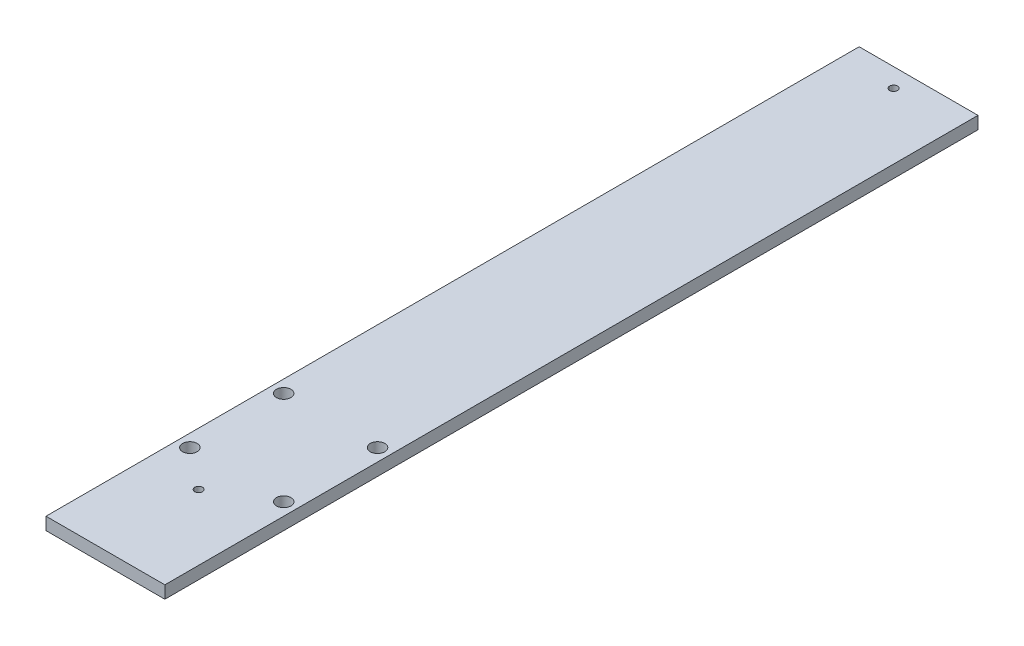
SolidWorks part; units mm, degrees
material "Alloy Steel"
ref_plane "Front" through (0, 0, 0) normal (0, 0, 1) x (1, 0, 0)
ref_plane "Top" through (0, 0, 0) normal (0, 1, 0) x (1, 0, 0)
ref_plane "Right" through (0, 0, 0) normal (1, 0, 0) x (0, 0, -1)
sketch "Sketch1" plane through (0, 0, 0) normal (0, 1, 0) x (1, 0, 0)
  line L1 (0, 0) -> (241.3, 0)
  line L2 (0, 0) -> (0, -1651)
  line L3 (0, -1651) -> (241.3, -1651)
  line L4 (241.3, 0) -> (241.3, -1651)
  dimension "D1" = 241.3
  dimension "D2" = 1651
extrude "Boss-Extrude1" add sketch "Sketch1" along normal blind 25.4
sketch "Sketch2" plane through (0, 25.4, 0) normal (0, 1, 0) x (1, 0, 0)
  line L0 (241.3, 0) -> (0, 0) construction
  line L1 (0, 0) -> (0, -1651) construction
  circle A0 centre (107.95, -38.1) radius 7.9375
  circle A1 centre (107.95, -1449.0573) radius 7.9375
  dimension "D1" = 15.875
  dimension "D2" = 15.875
  dimension "D3" = 1410.9573
  dimension "D4" = 38.1
  dimension "D5" = 107.95
extrude "Cut-Extrude1" cut sketch "Sketch2" against normal through all both and the other way through all
sketch "Sketch3" plane through (0, 0, 0) normal (0, -1, 0) x (1, 0, 0)
  circle A0 centre (215.9, 1193.8) radius 14.7295
  circle A1 centre (25.4, 1193.8) radius 14.7295
  circle A2 centre (25.4, 1384.3) radius 14.7295
  circle A3 centre (215.9, 1384.3) radius 14.7295
extrude "Cut-Extrude2" cut sketch "Sketch3" against normal through all
sketch "Sketch4" plane through (0, 0, 0) normal (0, -1, 0) x (1, 0, 0)
  line L0 (115.8875, 38.1) -> (100.0125, 38.1)
  circle A1 centre (107.95, 38.1) radius 7.9375 construction
  point P6 (107.95, 49.2724)
  point P7 (107.95, 38.1)
  point P8 (106.5331, 43.9632)
  point P9 (107.95, 46.0375)
  point P10 (109.4311, 45.8981)
  dimension "D1" = 15.875
split line "Split Line1"
sketch "Sketch5" plane through (0, 0, 0) normal (0, -1, 0) x (1, 0, 0)
  line L0 (115.8875, 1449.0573) -> (100.0125, 1449.0573)
  circle A0 centre (107.95, 1449.0573) radius 7.9375 construction
  dimension "D1" = 15.875
split line "Split Line2"
